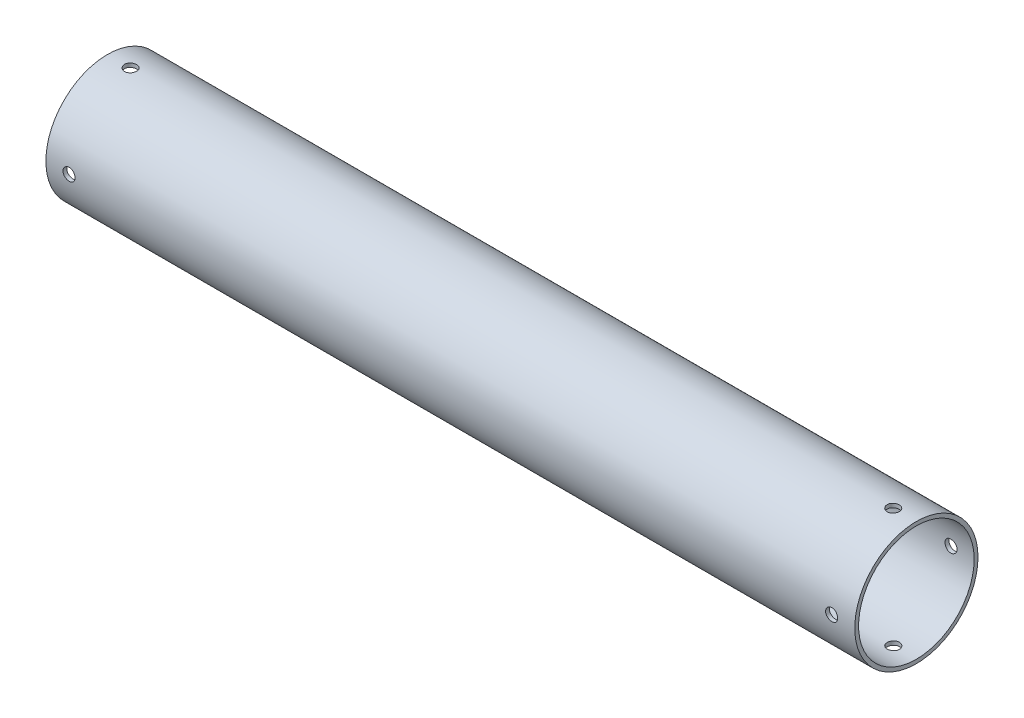
SolidWorks part; units mm, degrees
other "Exploded View1" [suppressed]
material "PC High Viscosity"
ref_plane "Front Plane" through (0, 0, 0) normal (0, 0, 1) x (1, 0, 0)
ref_plane "Top Plane" through (0, 0, 0) normal (0, 1, 0) x (1, 0, 0)
ref_plane "Right Plane" through (0, 0, 0) normal (1, 0, 0) x (0, 0, -1)
sketch "Sketch1" plane through (0, 0, 0) normal (1, 0, 0) x (0, 0, -1)
  circle A0 centre (0, 0) radius 25.4
  dimension "D1" = 50.8
extrude "Extrude-Thin1" add sketch "Sketch1" along normal mid plane 333.375 thin thin type one direction reverse wall 1.5875
sketch "Sketch2" plane through (0, 0, 0) normal (0, 0, 1) x (1, 0, 0)
  line L0 (-166.6875, -25.4) -> (166.6875, -25.4) construction
  line L1 (111.4135, -25.4) -> (132.4135, -25.4)
  line L2 (111.4135, -25.4) -> (111.4135, 25.4)
  line L3 (111.4135, 25.4) -> (132.4135, 25.4)
  line L4 (132.4135, -25.4) -> (132.4135, 25.4)
  line L5 (166.6875, 25.4) -> (-166.6875, 25.4) construction
  line L6 (166.6875, -25.4) -> (166.6875, 25.4) construction
  line L7 (0, 0) -> (0, 11.1276) construction
  line L8 (-132.4135, -25.4) -> (-132.4135, 25.4)
  line L9 (-111.4135, 25.4) -> (-132.4135, 25.4)
  line L10 (-111.4135, -25.4) -> (-111.4135, 25.4)
  line L11 (-111.4135, -25.4) -> (-132.4135, -25.4)
  dimension "D1" = 34.274
  dimension "D2" = 21
sketch "Sketch3" plane through (0, 0, 0) normal (0, 0, 1) x (1, 0, 0)
  line L0 (-166.6875, 25.4) -> (-166.6875, -25.4) construction
  line L1 (166.6875, -25.4) -> (166.6875, 25.4) construction
  circle A0 centre (-157.1625, 0) radius 2.4892
  circle A1 centre (157.1625, 0) radius 2.4892
  dimension "D1" = 4.9784
  dimension "D2" = 9.525
  dimension "D3" = 9.525
extrude "Cut-Extrude1" cut sketch "Sketch3" against normal through all both and the other way through all
sketch "Sketch4" plane through (0, 0, 0) normal (0, 1, 0) x (1, 0, 0)
  line L0 (-166.6875, 25.4) -> (-166.6875, -25.4) construction
  line L1 (166.6875, -23.8125) -> (166.6875, 23.8125) construction
  circle A0 centre (-157.1625, 0) radius 2.4892
  circle A1 centre (157.1625, 0) radius 2.4892
  dimension "D1" = 4.9784
  dimension "D2" = 9.525
  dimension "D3" = 9.525
extrude "Cut-Extrude2" cut sketch "Sketch4" against normal through all both and the other way through all
equation "\"D2@Sketch2\"=21mm"
